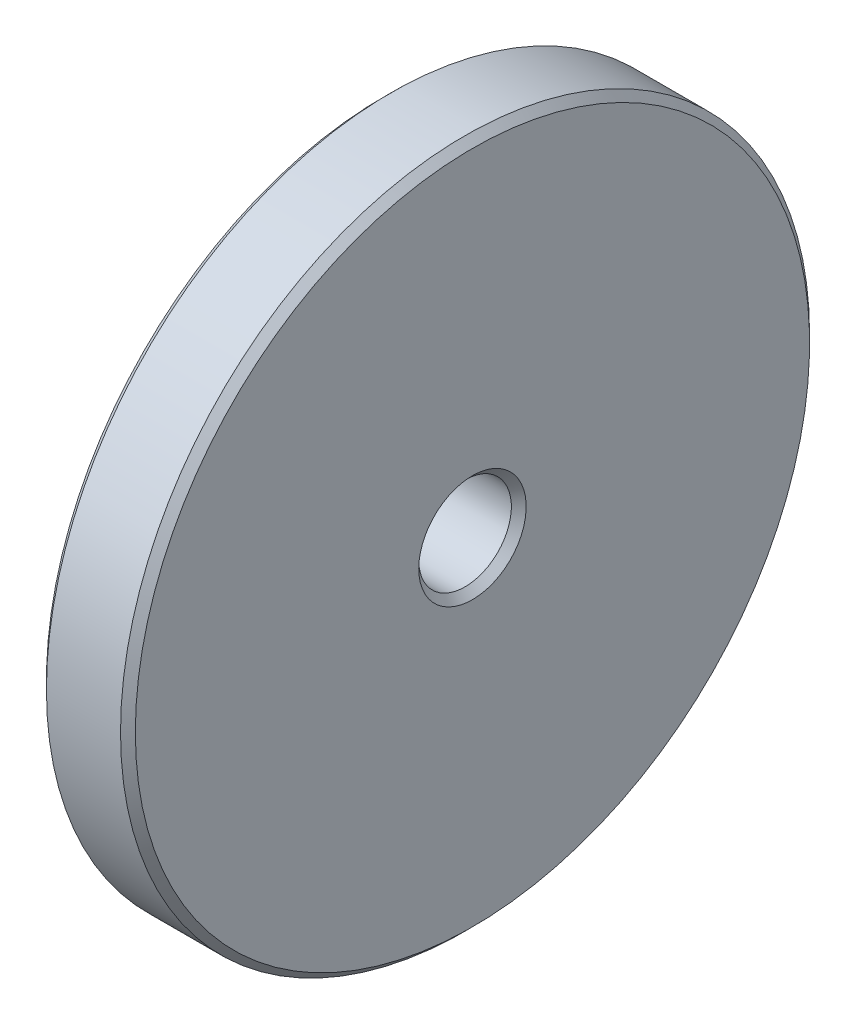
SolidWorks part; units mm, degrees
ref_plane "Front" through (0, 0, 0) normal (0, 0, 1) x (1, 0, 0)
ref_plane "Top" through (0, 0, 0) normal (0, 1, 0) x (1, 0, 0)
ref_plane "Right" through (0, 0, 0) normal (1, 0, 0) x (0, 0, -1)
sketch "Sketch1" plane through (0, 0, 0) normal (0, 0, 1) x (1, 0, 0)
  line L0 (-17.903, 0) -> (16.4933, 0) construction
  line L1 (-13.2384, 6.25) -> (-13.2384, 46.5)
  line L2 (-13.2384, 46.5) -> (-1.2384, 46.5)
  line L3 (-1.2384, 46.5) -> (-1.2384, 6.25)
  line L5 (-1.2384, 6.25) -> (-13.2384, 6.25)
  dimension "D1" = 12.5
  dimension "D2" = 93
  dimension "D3" = 12
revolve "Base-Revolve" add sketch "Sketch1" angle 360 about L0
chamfer "Sfazowanie1" distance 1 angle 45 4 edges at (-1.2384, 0, 6.25) (-1.2384, 0, 46.5) (-13.2384, 0, 46.5) (-13.2384, 0, 6.25)
